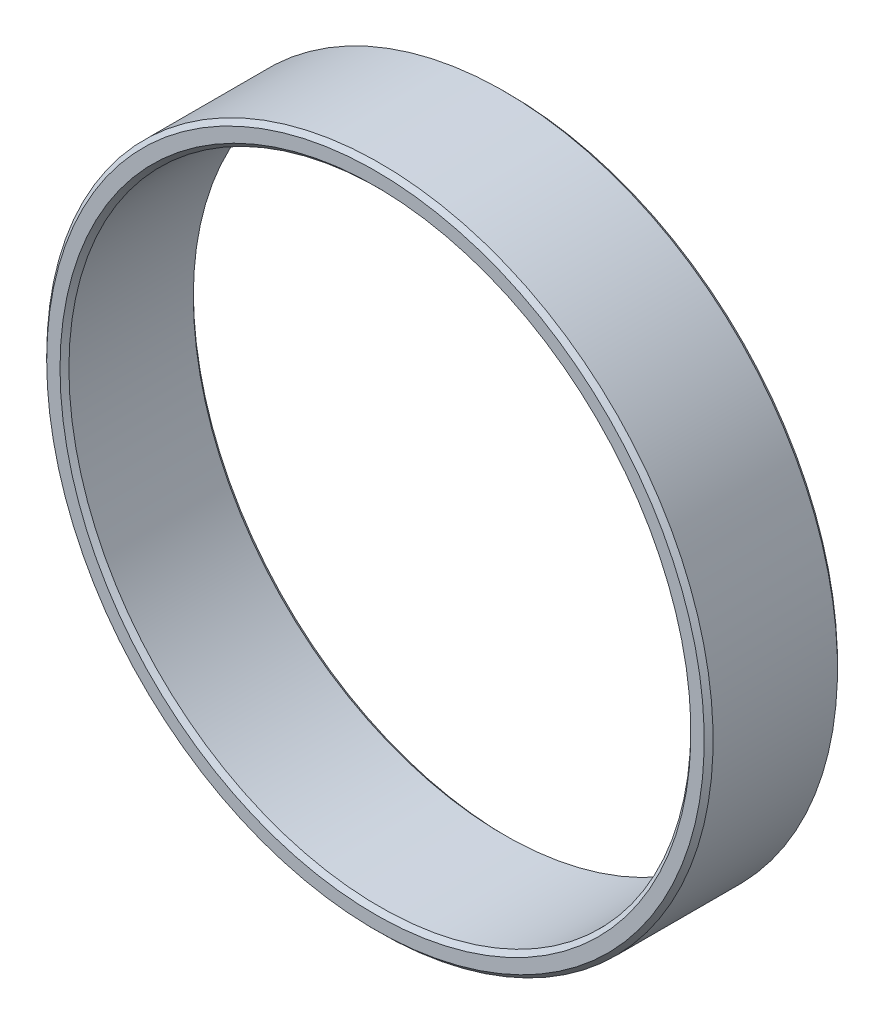
SolidWorks part; units mm, degrees
material "Copper"
ref_plane "Front Plane" through (0, 0, 0) normal (0, 0, 1) x (1, 0, 0)
ref_plane "Top Plane" through (0, 0, 0) normal (0, 1, 0) x (1, 0, 0)
ref_plane "Right Plane" through (0, 0, 0) normal (1, 0, 0) x (0, 0, -1)
sketch "Sketch1" plane through (0, 0, 0) normal (1, 0, 0) x (0, 0, -1)
  line L0 (0, 0) -> (-107.6704, 0) construction
  line L1 (-35.9044, 37) -> (-35.4044, 37.5)
  line L2 (-35.4044, 37.5) -> (-21.4044, 37.5)
  line L3 (-35.9044, 37) -> (-35.9044, 35.5)
  line L4 (-35.4044, 35) -> (-21.4044, 35)
  line L5 (-20.9044, 37) -> (-20.9044, 35.5)
  line L6 (-21.4044, 37.5) -> (-20.9044, 37)
  line L7 (-21.4044, 35) -> (-20.9044, 35.5)
  line L8 (-35.9044, 35.5) -> (-35.4044, 35)
  point P3 (-35.9044, 37.5)
  point P4 (-20.9044, 35)
  point P5 (-35.9044, 35)
  point P6 (-20.9044, 37.5)
  dimension "D1" = 75
  dimension "D2" = 70
  dimension "D3" = 15
  dimension "D4" = 0.5
  dimension "D5" = 45
  dimension "D6" = 0.5
  dimension "D7" = 45
  dimension "D8" = 0.5
  dimension "D9" = 45
  dimension "D10" = 0.5
  dimension "D11" = 45
revolve "Revolve1" add sketch "Sketch1" angle 360 about L0
